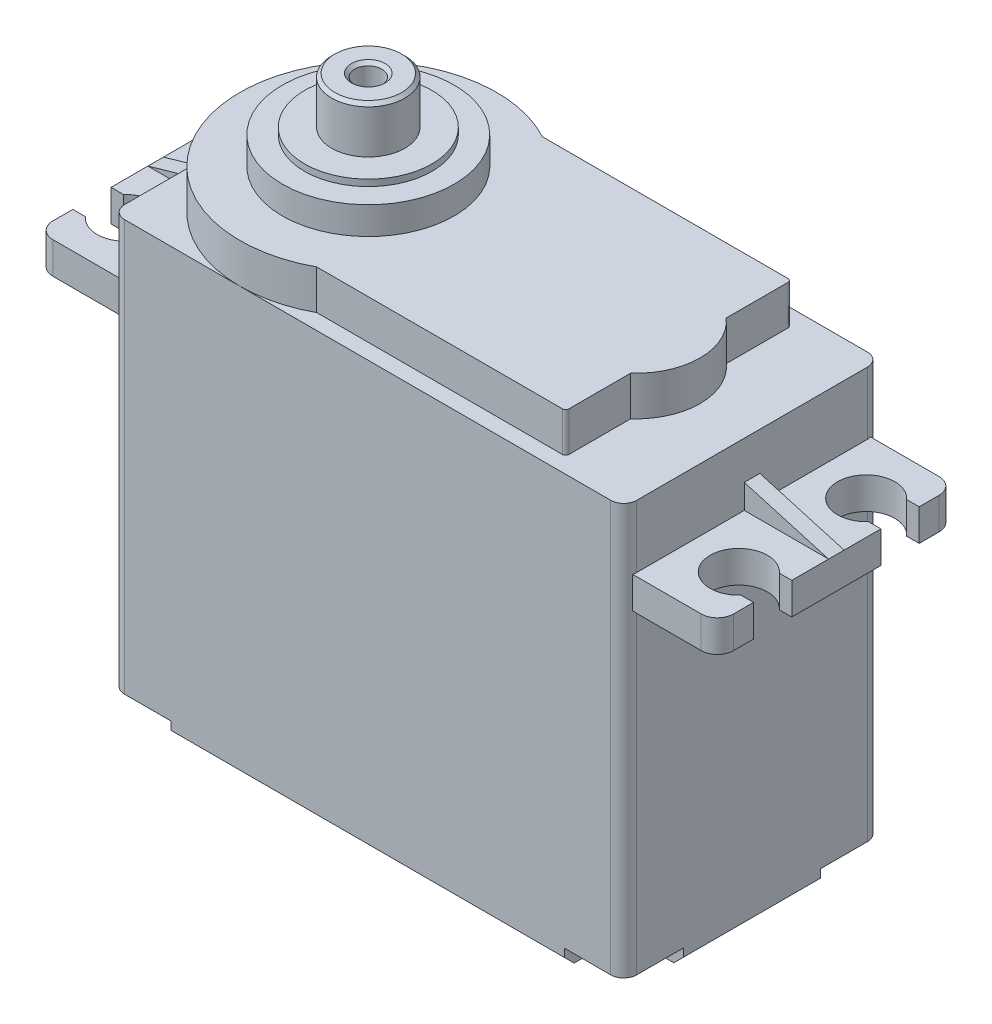
SolidWorks part; units mm, degrees
ref_plane "Front Plane" through (0, 0, 0) normal (0, 0, 1) x (1, 0, 0)
ref_plane "Top Plane" through (0, 0, 0) normal (0, 1, 0) x (1, 0, 0)
ref_plane "Right Plane" through (0, 0, 0) normal (1, 0, 0) x (0, 0, -1)
sketch "Sketch1" plane through (0, 0, 0) normal (0, 1, 0) x (1, 0, 0)
  line L0 (0, 9.0424) -> (0, -9.0424)
  line L1 (1.016, -10.0584) -> (39.116, -10.0584)
  line L2 (40.132, -9.0424) -> (40.132, 9.0424)
  line L3 (39.116, 10.0584) -> (1.016, 10.0584)
  arc A0 (39.116, 10.0584) -> (40.132, 9.0424) centre (39.116, 9.0424) cw
  arc A1 (40.132, -9.0424) -> (39.116, -10.0584) centre (39.116, -9.0424) cw
  arc A2 (1.016, -10.0584) -> (0, -9.0424) centre (1.016, -9.0424) cw
  arc A3 (0, 9.0424) -> (1.016, 10.0584) centre (1.016, 9.0424) cw
  point P7 (40.132, 10.0584)
  point P12 (0, -10.0584)
  point P15 (0, 10.0584)
  dimension "D4" = 1.016
  dimension "D1" = 20.1168
  dimension "D2" = 10.0584
  dimension "D3" = 40.132
extrude "Boss-Extrude1" add sketch "Sketch1" along normal blind 33.6042
sketch "Sketch2" plane through (0, 0, 0) normal (0, -1, 0) x (1, 0, 0)
  line L0 (20.066, 10.0584) -> (20.066, -10.0584) construction
  line L1 (1.016, 10.0584) -> (39.116, 10.0584) construction
  line L2 (39.116, -10.0584) -> (1.016, -10.0584) construction
  line L3 (0, 0) -> (40.132, 0) construction
  line L4 (40.132, 9.0424) -> (40.132, -9.0424) construction
  line L5 (4.6482, 10.0584) -> (4.6482, 7.3533)
  line L6 (35.4838, 10.0584) -> (35.4838, 7.3533)
  line L7 (0, -5.3721) -> (2.667, -5.3721)
  line L8 (0, 5.3721) -> (2.667, 5.3721)
  line L9 (37.465, 5.3721) -> (40.132, 5.3721)
  line L10 (4.6482, -7.3533) -> (4.6482, -10.0584)
  line L11 (0, 5.3721) -> (40.132, 5.3721) construction
  line L12 (37.465, -5.3721) -> (40.132, -5.3721)
  line L13 (4.6482, 10.0584) -> (4.6482, -10.0584) construction
  line L14 (35.4838, -7.3533) -> (35.4838, -10.0584)
  line L15 (0, -5.3721) -> (40.132, -5.3721) construction
  line L16 (0, -5.3721) -> (0, -9.0424)
  line L17 (35.4838, 10.0584) -> (35.4838, -10.0584) construction
  line L18 (35.4838, -10.0584) -> (39.116, -10.0584)
  line L19 (40.132, 5.3721) -> (40.132, 9.0424)
  line L20 (4.6482, 10.0584) -> (1.016, 10.0584)
  line L21 (40.132, -9.0424) -> (40.132, 9.0424)
  line L22 (39.116, 10.0584) -> (1.016, 10.0584)
  line L23 (0, 9.0424) -> (0, -9.0424)
  line L24 (1.016, -10.0584) -> (39.116, -10.0584)
  line L25 (40.132, -9.0424) -> (40.132, -5.3721)
  line L26 (39.116, 10.0584) -> (35.4838, 10.0584)
  line L27 (0, 9.0424) -> (0, 5.3721)
  line L28 (1.016, -10.0584) -> (4.6482, -10.0584)
  arc A0 (2.667, -5.3721) -> (4.6482, -7.3533) centre (2.667, -7.3533) cw
  arc A1 (35.4838, -7.3533) -> (37.465, -5.3721) centre (37.465, -7.3533) cw
  arc A2 (37.465, 5.3721) -> (35.4838, 7.3533) centre (37.465, 7.3533) cw
  arc A3 (4.6482, 7.3533) -> (2.667, 5.3721) centre (2.667, 7.3533) cw
  arc A8 (39.116, -10.0584) -> (40.132, -9.0424) centre (39.116, -9.0424) ccw
  arc A9 (40.132, 9.0424) -> (39.116, 10.0584) centre (39.116, 9.0424) ccw
  arc A10 (1.016, 10.0584) -> (0, 9.0424) centre (1.016, 9.0424) ccw
  arc A11 (0, -9.0424) -> (1.016, -10.0584) centre (1.016, -9.0424) ccw
  arc A12 (39.116, -10.0584) -> (40.132, -9.0424) centre (39.116, -9.0424) ccw
  arc A13 (40.132, 9.0424) -> (39.116, 10.0584) centre (39.116, 9.0424) ccw
  arc A14 (1.016, 10.0584) -> (0, 9.0424) centre (1.016, 9.0424) ccw
  arc A15 (0, -9.0424) -> (1.016, -10.0584) centre (1.016, -9.0424) ccw
  point P27 (35.4838, -5.3721)
  dimension "D5" = 1.9812
  dimension "D1" = 15.4178
  dimension "D2" = 15.4178
  dimension "D3" = 5.3721
  dimension "D4" = 5.3721
  dimension "D6" = 0
extrude "Cut-Extrude1" cut sketch "Sketch2" against normal blind 1.397
chamfer "Chamfer1" distance 0.762 angle 45 4 edges at (0, 0, 0) (20.066, 0, -10.0584) (40.132, 0, 0) (20.066, 0, 10.0584)
sketch "Sketch3" plane through (40.132, 0, 0) normal (1, 0, 0) x (0, 0, -1)
  line L1 (-9.3218, 28.702) -> (9.3218, 28.702)
  line L2 (-9.0424, 26.2128) -> (9.0424, 26.2128)
  line L3 (-9.3218, 26.2128) -> (9.3218, 26.2128)
  line L4 (0, 39.7789) -> (0, -7.6498) construction
  line L5 (-9.3218, 28.702) -> (-9.3218, 26.2128)
  line L6 (9.3218, 28.702) -> (9.3218, 26.2128)
  line L7 (-9.0424, 28.702) -> (9.0424, 28.702) construction
  line L8 (-9.3218, 39.7789) -> (-9.3218, -7.6498) construction
  line L9 (-9.0424, 26.2128) -> (9.0424, 26.2128) construction
  line L10 (9.3218, 39.7789) -> (9.3218, -7.6498) construction
  dimension "D1" = 7.3914
  dimension "D2" = 9.3218
  dimension "D3" = 2.4892
  dimension "D4" = 9.3218
extrude "Boss-Extrude2" add sketch "Sketch3" along normal mid plane 13.208
sketch "Sketch4" plane through (0, 0, 0) normal (-1, 0, 0) x (0, 0, 1)
  line L0 (9.0424, 26.2128) -> (-9.0424, 26.2128) construction
  line L1 (-9.3218, 26.2128) -> (-9.3218, 28.702) construction
  line L2 (-9.0424, 28.702) -> (9.0424, 28.702) construction
  line L3 (9.3218, 28.702) -> (9.3218, 26.2128) construction
  line L4 (9.3218, 26.2128) -> (-9.3218, 26.2128)
  line L5 (-9.3218, 26.2128) -> (-9.3218, 28.702)
  line L6 (-9.3218, 28.702) -> (9.3218, 28.702)
  line L7 (9.3218, 28.702) -> (9.3218, 26.2128)
extrude "Boss-Extrude3" add sketch "Sketch4" along normal mid plane 13.208
fillet "Fillet1" radius 1.27 4 edges at (-6.604, 27.4574, 9.3218) (-6.604, 27.4574, -9.3218) (46.736, 27.4574, -9.3218) (46.736, 27.4574, 9.3218)
sketch "Sketch5" plane through (0, 28.702, 0) normal (0, 1, 0) x (1, 0, 0)
  line L0 (-9.1456, 0) -> (53.3851, 0) construction
  line L1 (20.066, 10.0584) -> (20.066, -10.0584) construction
  line L2 (39.116, 10.0584) -> (1.016, 10.0584) construction
  line L3 (1.016, -10.0584) -> (39.116, -10.0584) construction
  line L4 (-9.1456, -4.9911) -> (-3.9497, -4.9911) construction
  line L5 (-9.1456, 4.9911) -> (-3.9497, 4.9911) construction
  line L6 (-3.9497, 10.0584) -> (-3.9497, 4.9911) construction
  line L7 (44.0817, 10.0584) -> (44.0817, 4.9911) construction
  line L8 (-3.9497, -4.9911) -> (-3.9497, -10.0584) construction
  line L9 (44.0817, -4.9911) -> (44.0817, -10.0584) construction
  line L10 (-3.9497, 10.0584) -> (-3.9497, -10.0584) construction
  line L11 (44.0817, -4.9911) -> (53.3851, -4.9911) construction
  line L12 (44.0817, 10.0584) -> (44.0817, -10.0584) construction
  line L13 (44.0817, 4.9911) -> (53.3851, 4.9911) construction
  line L14 (-9.1456, -4.9911) -> (53.3851, -4.9911) construction
  line L15 (-6.604, 3.4925) -> (-5.6252, 3.4925)
  line L16 (-9.1456, 4.9911) -> (53.3851, 4.9911) construction
  line L17 (-6.604, -6.4897) -> (-5.6252, -6.4897)
  line L18 (45.7572, -6.4897) -> (46.736, -6.4897)
  line L19 (45.7572, 3.4925) -> (46.736, 3.4925)
  line L20 (-6.604, 6.4897) -> (-5.6252, 6.4897)
  line L21 (-6.604, -3.4925) -> (-5.6252, -3.4925)
  line L22 (45.7572, -3.4925) -> (46.736, -3.4925)
  line L23 (45.7572, 6.4897) -> (46.736, 6.4897)
  line L24 (-6.604, -8.0518) -> (-6.604, 8.0518) construction
  line L25 (46.736, 8.0518) -> (46.736, -8.0518) construction
  line L26 (-6.604, -6.4897) -> (-6.604, -3.4925)
  line L27 (46.736, 6.4897) -> (46.736, 3.4925)
  line L28 (-9.1456, 6.4897) -> (-3.9497, 6.4897) construction
  line L29 (-9.1456, -6.4897) -> (-3.9497, -6.4897) construction
  line L30 (44.0817, -6.4897) -> (53.3851, -6.4897) construction
  line L31 (44.0817, 6.4897) -> (53.3851, 6.4897) construction
  line L32 (46.736, -3.4925) -> (46.736, -6.4897)
  line L33 (44.0817, 3.4925) -> (53.3851, 3.4925) construction
  line L34 (44.0817, -3.4925) -> (53.3851, -3.4925) construction
  line L35 (-9.1456, -3.4925) -> (-3.9497, -3.4925) construction
  line L36 (-9.1456, 3.4925) -> (-3.9497, 3.4925) construction
  line L37 (-6.604, 3.4925) -> (-6.604, 6.4897)
  arc A0 (-5.6252, 3.4925) -> (-5.6252, 6.4897) centre (-3.9497, 4.9911) ccw
  arc A1 (-5.6252, -6.4897) -> (-5.6252, -3.4925) centre (-3.9497, -4.9911) ccw
  arc A2 (45.7572, -3.4925) -> (45.7572, -6.4897) centre (44.0817, -4.9911) ccw
  arc A3 (45.7572, 6.4897) -> (45.7572, 3.4925) centre (44.0817, 4.9911) ccw
  dimension "D5" = 4.4958
  dimension "D1" = 4.9911
  dimension "D2" = 4.9911
  dimension "D3" = 24.0157
  dimension "D4" = 24.0157
  dimension "D6" = 1.4986
  dimension "D7" = 1.4986
extrude "Cut-Extrude2" cut sketch "Sketch5" against normal blind 3.048
sketch "Sketch6" plane through (0, 28.702, 0) normal (0, 1, 0) x (1, 0, 0)
  line L0 (-7.6959, 0) -> (49.9058, 0) construction
  line L1 (-6.604, -0.6096) -> (0, -0.6096)
  line L2 (-6.604, 0.6096) -> (0, 0.6096)
  line L3 (-6.604, -3.4925) -> (-6.604, 3.4925) construction
  line L4 (0, 9.0424) -> (0, -9.0424) construction
  line L5 (40.132, -9.0424) -> (40.132, 9.0424) construction
  line L6 (46.736, 3.4925) -> (46.736, -3.4925) construction
  line L7 (-6.604, -0.6096) -> (-6.604, 0.6096)
  line L8 (0, 0.6096) -> (0, -0.6096)
  line L9 (40.132, -0.6096) -> (40.132, 0.6096)
  line L10 (46.736, 0.6096) -> (46.736, -0.6096)
  line L11 (-7.6959, 0.6096) -> (49.9058, 0.6096) construction
  line L12 (-7.6959, -0.6096) -> (49.9058, -0.6096) construction
  line L13 (40.132, 0.6096) -> (46.736, 0.6096)
  line L14 (40.132, -0.6096) -> (46.736, -0.6096)
  dimension "D1" = 0.6096
  dimension "D2" = 0.6096
extrude "Boss-Extrude4" add sketch "Sketch6" along normal blind 1.905
sketch "Sketch7" plane through (0, 0, 0.6096) normal (0, 0, 1) x (1, 0, 0)
  line L0 (40.132, 30.607) -> (46.736, 28.702)
  line L1 (0, 30.607) -> (-6.604, 28.702)
  line L4 (-6.604, 28.702) -> (0, 28.702)
  line L5 (0, 28.702) -> (0, 30.607)
  line L6 (0, 30.607) -> (-6.604, 30.607)
  line L7 (-6.604, 30.607) -> (-6.604, 28.702)
  line L10 (0, 30.607) -> (-6.604, 30.607)
  line L11 (-6.604, 30.607) -> (-6.604, 28.702)
  line L12 (40.132, 28.702) -> (46.736, 28.702)
  line L13 (46.736, 28.702) -> (46.736, 30.607)
  line L14 (46.736, 30.607) -> (40.132, 30.607)
  line L15 (40.132, 30.607) -> (40.132, 28.702)
  line L17 (46.736, 28.702) -> (46.736, 30.607)
  line L18 (46.736, 30.607) -> (40.132, 30.607)
  dimension "D1" = 0
  dimension "D2" = 0
extrude "Cut-Extrude3" cut sketch "Sketch7" against normal blind 1.905
sketch "Sketch8" plane through (0, 33.6042, 0) normal (0, 1, 0) x (1, 0, 0)
  line L0 (-8.5657, 0) -> (49.6158, 0) construction
  line L1 (14.8584, -8.8392) -> (34.1122, -8.8392)
  line L2 (14.8584, 8.8392) -> (34.1122, 8.8392)
  line L4 (-8.5657, 8.8392) -> (49.6158, 8.8392) construction
  line L5 (10.0584, 9.0424) -> (10.0584, -9.0424)
  line L6 (10.0584, 9.0424) -> (10.0584, -9.0424) construction
  line L7 (-8.5657, -8.8392) -> (49.6158, -8.8392) construction
  line L8 (34.3662, -3.7413) -> (34.3662, -8.5852)
  line L9 (34.3662, 9.0424) -> (34.3662, -9.0424)
  line L10 (34.3662, 8.5852) -> (34.3662, 3.7413)
  arc A0 (14.8584, 8.8392) -> (14.8584, -8.8392) centre (10.0584, 0) ccw
  arc A1 (34.3662, -3.7413) -> (34.3662, 3.7413) centre (31.0626, 0) ccw
  arc A2 (34.1122, -8.8392) -> (34.3662, -8.5852) centre (34.1122, -8.5852) ccw
  arc A3 (34.3662, 8.5852) -> (34.1122, 8.8392) centre (34.1122, 8.5852) ccw
  dimension "D5" = 9.9822
  dimension "D6" = 0.254
  dimension "D1" = 10.0584
  dimension "D2" = 8.8392
  dimension "D3" = 8.8392
  dimension "D4" = 34.3662
extrude "Boss-Extrude5" add sketch "Sketch8" along normal blind 3.0988
sketch "Sketch9" plane through (0, 36.703, 0) normal (0, 1, 0) x (1, 0, 0)
  circle A0 centre (10.0584, 0) radius 6.731
  dimension "D1" = 13.462
extrude "Boss-Extrude6" add sketch "Sketch9" along normal blind 2.159
sketch "Sketch10" plane through (0, 38.862, 0) normal (0, 1, 0) x (1, 0, 0)
  circle A0 centre (10.0584, 0) radius 4.9911
  dimension "D1" = 9.9822
extrude "Boss-Extrude7" add sketch "Sketch10" along normal blind 0.508
sketch "Sketch11" plane through (0, 39.37, 0) normal (0, 1, 0) x (1, 0, 0)
  circle A0 centre (10.0584, 0) radius 2.8702
  dimension "D1" = 5.7404
extrude "Boss-Extrude8" add sketch "Sketch11" along normal blind 3.6576
sketch "Sketch12" plane through (0, 43.0276, 0) normal (0, 1, 0) x (1, 0, 0)
  circle A0 centre (10.0584, 0) radius 1.0668
  dimension "D1" = 2.1336
extrude "Cut-Extrude4" cut sketch "Sketch12" against normal blind 5.08
chamfer "Chamfer2" distance 0.254 angle 45 2 edges at (10.0584, 43.0276, 2.8702) (10.0584, 43.0276, 1.0668)
scale "Scale1" scale about centroid uniform scaling yes scale factor 0.6
